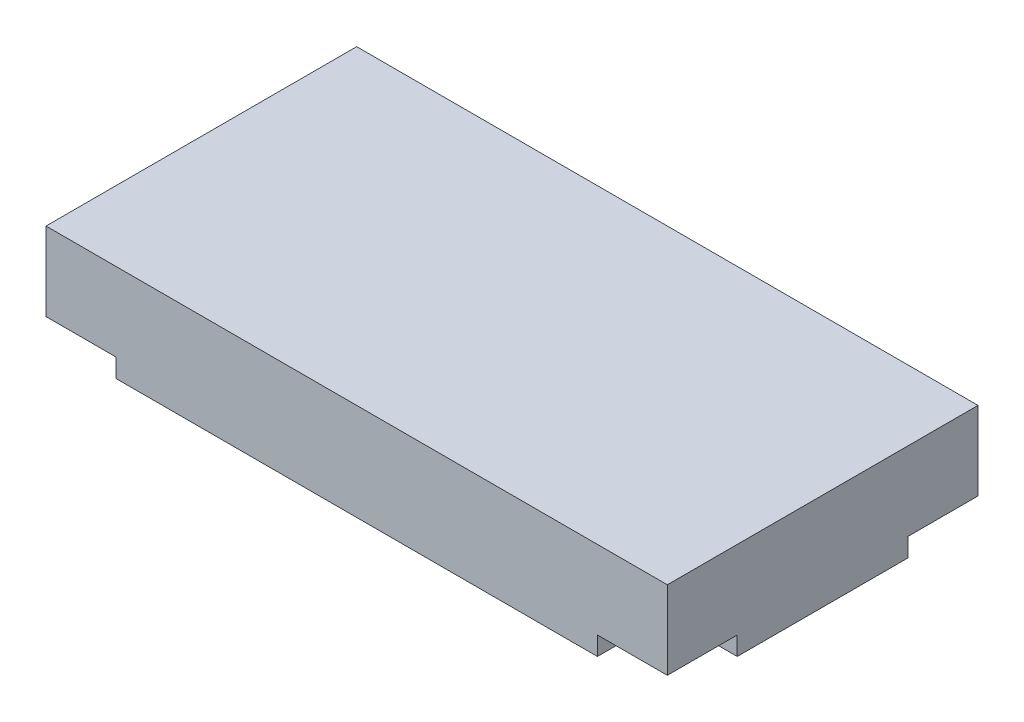
SolidWorks part; units mm, degrees
material "ABS"
ref_plane "Alzado" through (0, 0, 0) normal (0, 0, 1) x (1, 0, 0)
ref_plane "Planta" through (0, 0, 0) normal (0, 1, 0) x (1, 0, 0)
ref_plane "Vista lateral" through (0, 0, 0) normal (1, 0, 0) x (0, 0, -1)
sketch "Croquis base" plane through (0, 0, 0) normal (0, 1, 0) x (1, 0, 0)
  line L1 (-20, 10) -> (20, 10)
  line L2 (-20, 10) -> (-20, -10)
  line L3 (-20, -10) -> (20, -10)
  line L4 (20, 10) -> (20, -10)
  line L5 (-20, 10) -> (20, -10) construction
  line L6 (-20, -10) -> (20, 10) construction
  point P0 (0, 0)
  dimension "D1" = 20
  dimension "D2" = 40
extrude "Saliente-Extruir1" add sketch "Croquis base" along normal blind 6.25
sketch "Croquis base detalles" plane through (0, 0, 0) normal (0, -1, 0) x (1, 0, 0)
  line L0 (0, 10) -> (0, -10) construction
  line L1 (-20, 10) -> (20, 10) construction
  line L2 (20, -10) -> (-20, -10) construction
  line L3 (-20, 0) -> (20, 0) construction
  line L4 (-20, -10) -> (-20, 10) construction
  line L5 (20, 10) -> (20, -10) construction
  line L6 (15.5, 10) -> (15.5, 7.75)
  line L7 (-20, 10) -> (-15.5, 10)
  line L8 (-20, 10) -> (-20, 5.5)
  line L9 (-20, 5.5) -> (-17.75, 5.5)
  line L10 (-15.5, 10) -> (-15.5, 7.75)
  line L11 (20, 5.5) -> (17.75, 5.5)
  line L12 (20, 10) -> (20, 5.5)
  line L13 (20, 10) -> (15.5, 10)
  line L14 (20, -10) -> (15.5, -10)
  line L15 (20, -10) -> (20, -5.5)
  line L16 (20, -5.5) -> (17.75, -5.5)
  line L17 (-15.5, -10) -> (-15.5, -7.75)
  line L18 (-20, -5.5) -> (-17.75, -5.5)
  line L19 (-20, -10) -> (-20, -5.5)
  line L20 (-20, -10) -> (-15.5, -10)
  line L21 (15.5, -10) -> (15.5, -7.75)
  arc A0 (-15.5, 7.75) -> (-17.75, 5.5) centre (-17.75, 7.75) cw
  arc A1 (15.5, 7.75) -> (17.75, 5.5) centre (17.75, 7.75) ccw
  arc A2 (15.5, -7.75) -> (17.75, -5.5) centre (17.75, -7.75) cw
  arc A3 (-15.5, -7.75) -> (-17.75, -5.5) centre (-17.75, -7.75) ccw
  point P19 (-15.5, 5.5)
  point P26 (15.5, 5.5)
  point P39 (15.5, -5.5)
  point P40 (-15.5, -5.5)
  dimension "D3" = 2.25
  dimension "D1" = 4.5
  dimension "D2" = 4.5
extrude "Cortar-Extruir1" cut sketch "Croquis base detalles" against normal blind 1.2
